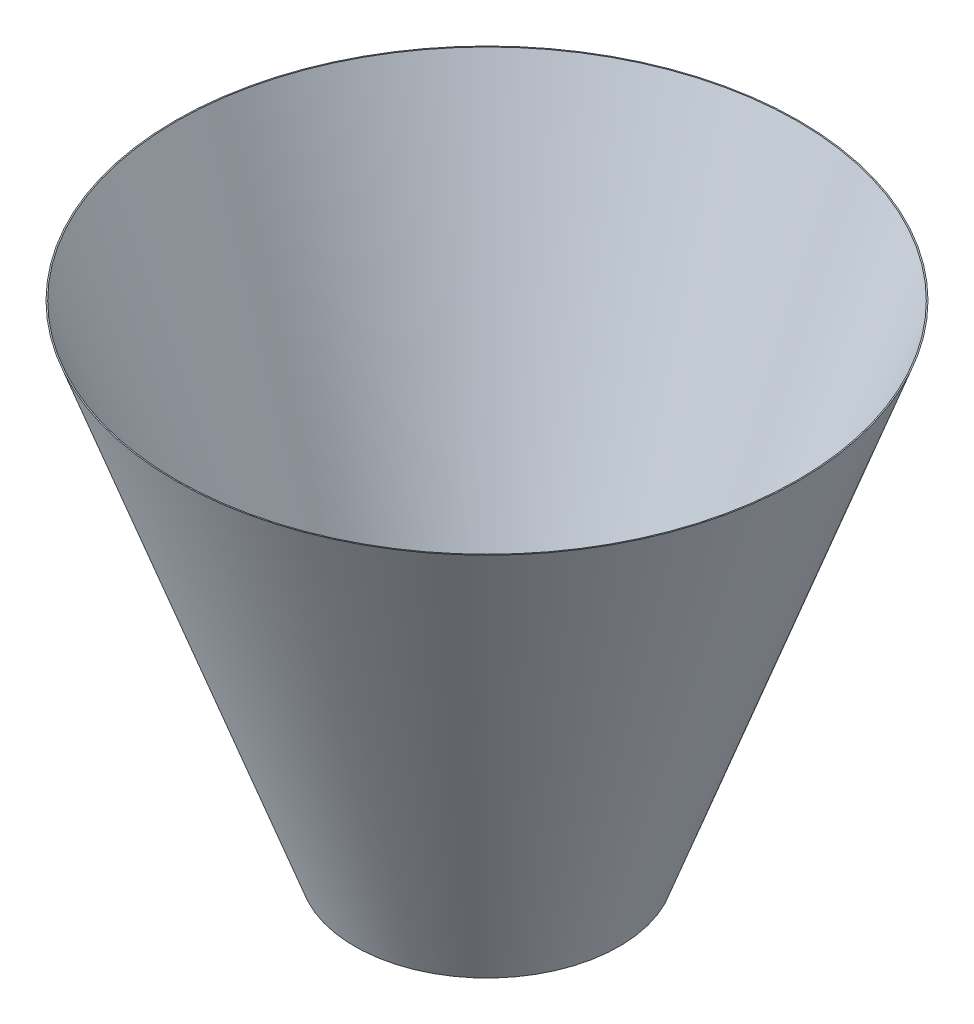
SolidWorks part; units mm, degrees
ref_plane "Front Plane" through (0, 0, 0) normal (0, 0, 1) x (1, 0, 0)
ref_plane "Top Plane" through (0, 0, 0) normal (0, 1, 0) x (1, 0, 0)
ref_plane "Right Plane" through (0, 0, 0) normal (1, 0, 0) x (0, 0, -1)
sketch "Sketch1" plane through (0, 0, 0) normal (0, 0, 1) x (1, 0, 0)
  line L0 (0, 0) -> (0, 311372.2135) construction
  line L1 (375.3656, 0) -> (889, 1411.1988)
  line L2 (0, 0) -> (311372.2135, 0) construction
  line L3 (375.3656, 0) -> (378.7444, 0)
  line L4 (378.7444, 0) -> (892.3788, 1411.1988)
  line L5 (892.3788, 1411.1988) -> (889, 1411.1988)
  dimension "D1" = 375.3656
  dimension "D2" = 70
  dimension "D3" = 889
  dimension "D4" = 3.175
revolve "Revolve1" add sketch "Sketch1" angle 360 about L0
